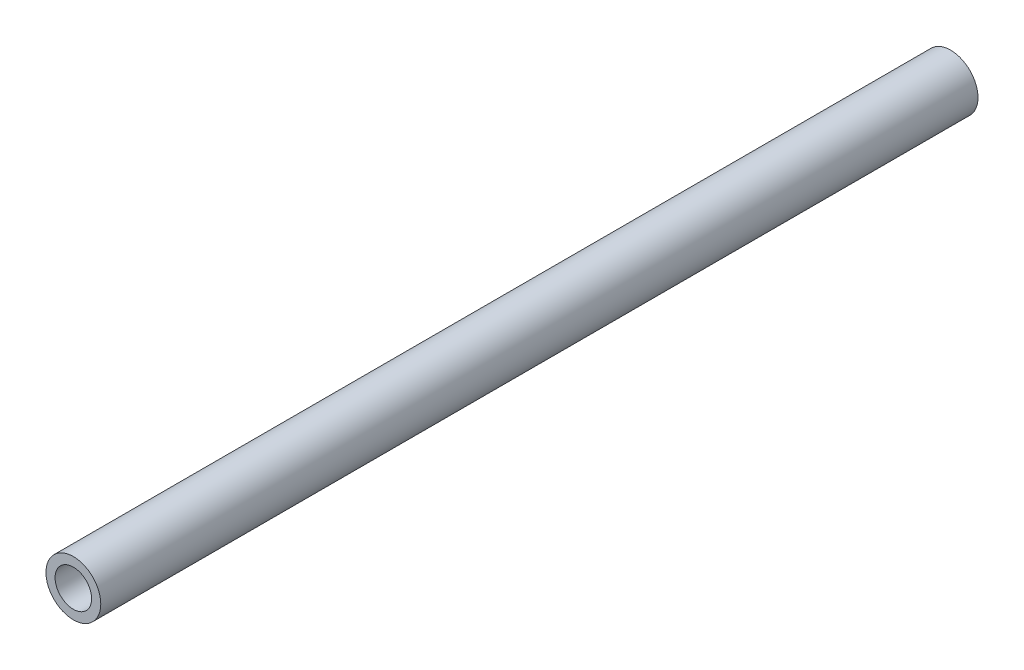
SolidWorks part; units mm, degrees
material "1060 Alloy"
ref_plane "Front Plane" through (0, 0, 0) normal (0, 0, 1) x (1, 0, 0)
ref_plane "Top Plane" through (0, 0, 0) normal (0, 1, 0) x (1, 0, 0)
ref_plane "Right Plane" through (0, 0, 0) normal (1, 0, 0) x (0, 0, -1)
sketch "Sketch1" plane through (0, 0, 0) normal (0, 0, 1) x (1, 0, 0)
  circle A0 centre (0, 0) radius 3
  circle A1 centre (0, 0) radius 2
  dimension "D1" = 6
  dimension "D2" = 1
extrude "Boss-Extrude1" add sketch "Sketch1" along normal blind 96
ref_plane "Plane1" through (0, 0, 48) normal (0, 0, 1) x (1, 0, 0)
